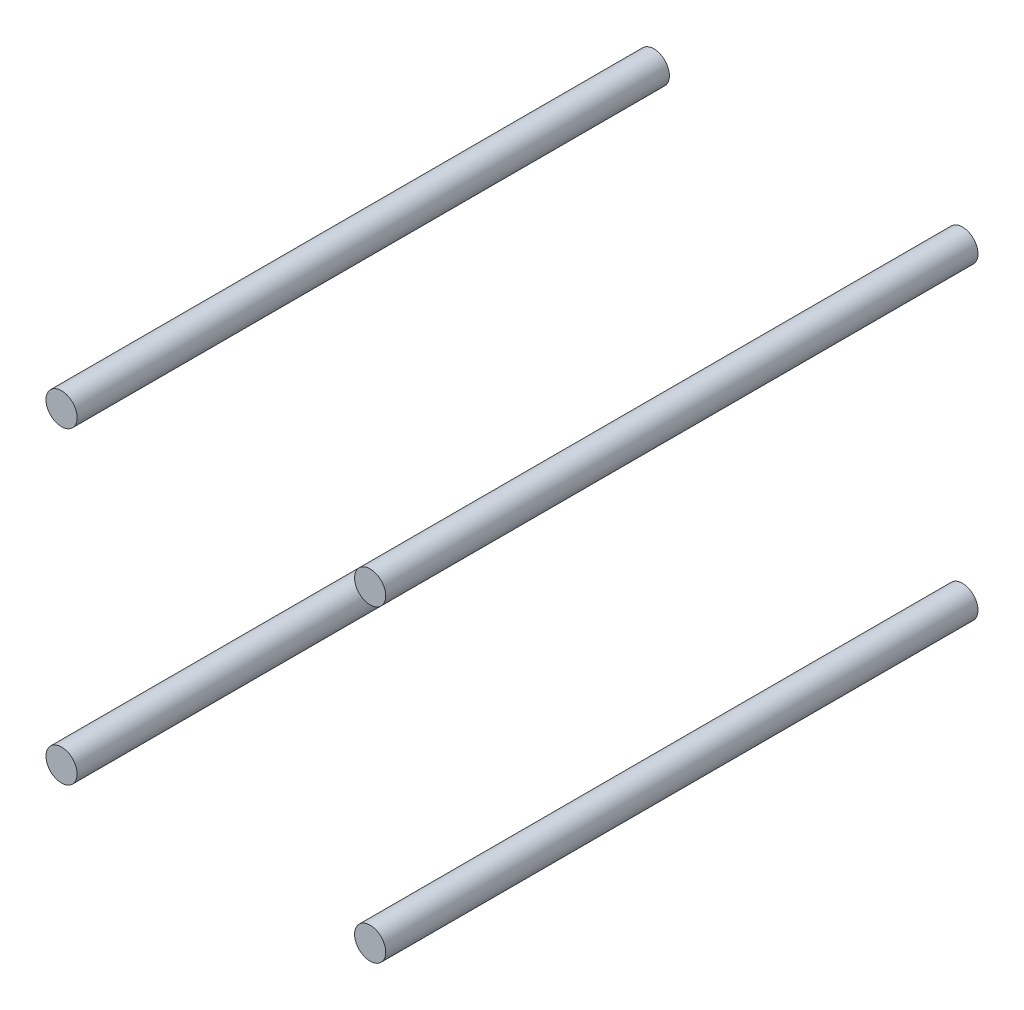
SolidWorks part; units mm, degrees
ref_plane "前视基准面" through (0, 0, 0) normal (0, 0, 1) x (1, 0, 0)
ref_plane "上视基准面" through (0, 0, 0) normal (0, 1, 0) x (1, 0, 0)
ref_plane "右视基准面" through (0, 0, 0) normal (1, 0, 0) x (0, 0, -1)
other "Configuration Table"
sketch "草图1" plane through (0, 0, 0) normal (0, 0, 1) x (1, 0, 0)
  circle A0 centre (24.7487, 24.7487) radius 2.5
  circle A1 centre (-24.7487, 24.7487) radius 2.5
  circle A2 centre (-24.7487, -24.7487) radius 2.5
  circle A3 centre (24.7487, -24.7487) radius 2.5
extrude "凸台-拉伸1" add sketch "草图1" against normal blind 95
